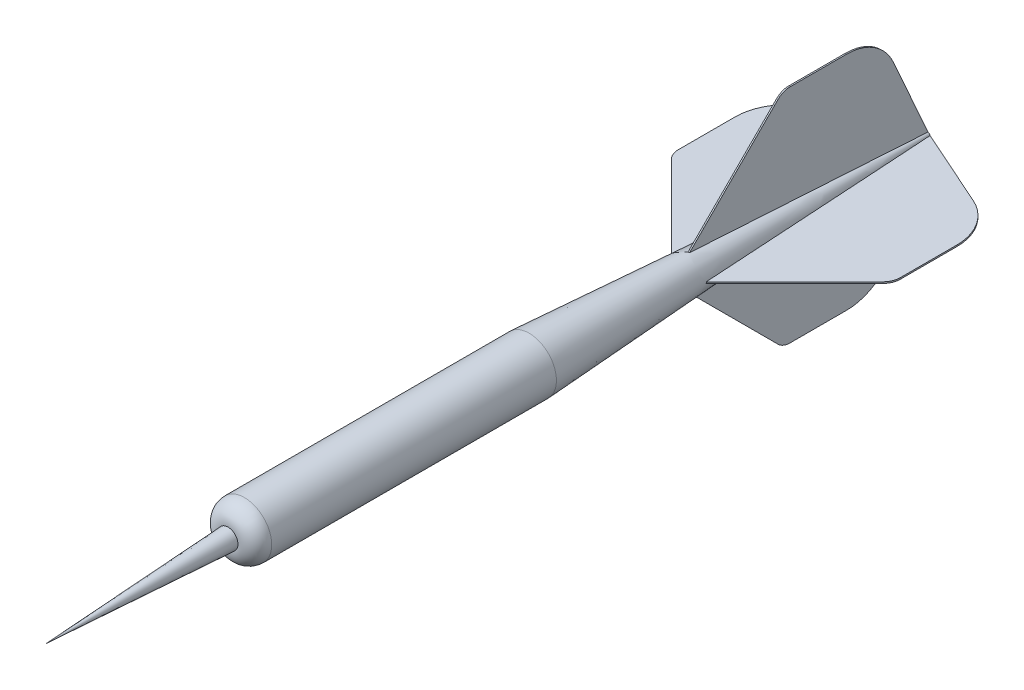
SolidWorks part; units mm, degrees
ref_plane "Front" through (0, 0, 0) normal (0, 0, 1) x (1, 0, 0)
ref_plane "Top" through (0, 0, 0) normal (0, 1, 0) x (1, 0, 0)
ref_plane "Right" through (0, 0, 0) normal (1, 0, 0) x (0, 0, -1)
sketch "Sketch1" plane through (0, 0, 0) normal (1, 0, 0) x (0, 0, -1)
  line L0 (0, 0) -> (-32, 0)
  line L1 (-32, 0) -> (0, 1.75)
  line L2 (2.8878, 4.8) -> (52.94, 4.8)
  line L3 (52.94, 4.8) -> (122.94, 0.5)
  line L4 (122.94, 0.5) -> (122.94, 0)
  line L5 (122.94, 0) -> (0, 0)
  line L6 (-32, 0) -> (-39.4145, 0) construction
  arc A0 (0, 1.75) -> (2.8878, 4.8) centre (2.8878, 1.9079) cw
  point P6 (0, 2.3209)
  point P10 (-39.4145, 0)
  dimension "D1" = 154.94
  dimension "D2" = 0.5
  dimension "D3" = 3.5
  dimension "D4" = 9.6
  dimension "D5" = 32
  dimension "D6" = 70
revolve "Dart" add sketch "Sketch1" angle 360 about L5
sketch "Sketch3" plane through (0, 0, 0) normal (1, 0, 0) x (0, 0, -1)
  line L0 (77.94, 0) -> (96.5613, 18.6213)
  line L1 (122.94, 0) -> (209.5416, 0) construction
  line L2 (98.6826, 19.5) -> (108.636, 19.5)
  line L4 (122.94, 0) -> (77.94, 0)
  line L5 (116.8579, 14.1606) -> (122.94, 0.5)
  line L6 (122.94, 0.5) -> (122.94, 0)
  line L7 (122.94, -0.5) -> (122.94, 0.5) construction
  arc A0 (96.5613, 18.6213) -> (98.6826, 19.5) centre (98.6826, 16.5) cw
  arc A1 (108.636, 19.5) -> (116.8579, 14.1606) centre (108.636, 10.5) cw
  point P0 (117.1222, 14.1125)
  dimension "D3" = 3
  dimension "D6" = 9
  dimension "D1" = 39
  dimension "D2" = 45
  dimension "D4" = 45
  dimension "D5" = 66
extrude "Flight" add sketch "Sketch3" along normal mid plane 0.25
pattern_circular "Flights" count 4 over 360 about axis through (0, 0, 0) along (0, 0, 1) of "Flight"
sketch "Sketch4" plane through (0, 0, 0) normal (0, 0, 1) x (1, 0, 0)
  line L0 (15.5733, 0) -> (0, 0) construction
  line L1 (0, 0) -> (14.4278, 14.4278) construction
  dimension "D1" = 45
sketch "Sketch6" plane through (0, 0, 0) normal (1, 0, 0) x (0, 0, -1)
  line L0 (0, 0) -> (21.0498, 0) construction
ref_plane "45 Degreen Plane" through (0, 0, 0) normal (-0.7071, 0.7071, 0) x (0.7071, 0.7071, 0)
sketch "Pocket Guide" plane through (0, 0, 0) normal (0, 0, 1) x (1, 0, 0)
  line L0 (0, 20) -> (0, 0) construction
  line L1 (0, 0) -> (20, 0) construction
  line L2 (-0.05, 20) -> (0.05, 20)
  line L3 (-0.75, 5.099) -> (-0.75, 19.3)
  line L4 (0.75, 19.3) -> (0.75, 5.099)
  line L5 (20, 0.05) -> (20, -0.05)
  line L6 (19.3, -0.75) -> (5.099, -0.75)
  line L7 (19.3, 0.75) -> (5.099, 0.75)
  line L8 (-5.099, 0.75) -> (-19.3, 0.75)
  line L9 (-20, 0.05) -> (-20, -0.05)
  line L10 (-19.3, -0.75) -> (-5.099, -0.75)
  line L11 (0.75, -5.099) -> (0.75, -19.3)
  line L12 (0.05, -20) -> (-0.05, -20)
  line L13 (-0.75, -19.3) -> (-0.75, -5.099)
  arc A0 (-4.6134, -1.131) -> (-1.131, -4.6134) centre (0, 0) ccw
  arc A1 (1.131, -4.6134) -> (4.6134, -1.131) centre (0, 0) ccw
  arc A2 (4.6134, 1.131) -> (1.131, 4.6134) centre (0, 0) ccw
  arc A3 (-1.131, 4.6134) -> (-4.6134, 1.131) centre (0, 0) ccw
  arc A4 (-0.05, 20) -> (-0.75, 19.3) centre (-0.05, 19.3) ccw
  arc A5 (0.05, 20) -> (0.75, 19.3) centre (0.05, 19.3) cw
  arc A6 (20, 0.05) -> (19.3, 0.75) centre (19.3, 0.05) ccw
  arc A7 (20, -0.05) -> (19.3, -0.75) centre (19.3, -0.05) cw
  arc A8 (0.75, -19.3) -> (0.05, -20) centre (0.05, -19.3) cw
  arc A9 (-0.05, -20) -> (-0.75, -19.3) centre (-0.05, -19.3) cw
  arc A10 (-20, -0.05) -> (-19.3, -0.75) centre (-19.3, -0.05) ccw
  arc A11 (-19.3, 0.75) -> (-20, 0.05) centre (-19.3, 0.05) ccw
  arc A12 (-0.75, 5.099) -> (-1.131, 4.6134) centre (-1.25, 5.099) cw
  arc A13 (0.75, 5.099) -> (1.131, 4.6134) centre (1.25, 5.099) ccw
  arc A14 (5.099, 0.75) -> (4.6134, 1.131) centre (5.099, 1.25) cw
  arc A15 (5.099, -0.75) -> (4.6134, -1.131) centre (5.099, -1.25) ccw
  arc A16 (0.75, -5.099) -> (1.131, -4.6134) centre (1.25, -5.099) cw
  arc A17 (-0.75, -5.099) -> (-1.131, -4.6134) centre (-1.25, -5.099) ccw
  arc A18 (-5.099, -0.75) -> (-4.6134, -1.131) centre (-5.099, -1.25) cw
  arc A19 (-5.099, 0.75) -> (-4.6134, 1.131) centre (-5.099, 1.25) ccw
  point P30 (20, 0.75)
  point P33 (20, -0.75)
  point P44 (-0.75, 4.6904)
  point P47 (0.75, 4.6904)
  point P50 (4.6904, 0.75)
  point P53 (4.6904, -0.75)
  point P56 (0.75, -4.6904)
  dimension "D1" = 9.5
  dimension "D4" = 0.7
  dimension "D5" = 0.5
  dimension "D2" = 40
  dimension "D3" = 1.5
sketch "Pin Pocket Guide" plane through (0, 0, 0) normal (0, 0, 1) x (1, 0, 0)
  circle A0 centre (0, 0) radius 2.5
  dimension "D1" = 5
sketch "Shaft Pocket Guide" plane through (0, 0, 0) normal (0, 0, 1) x (1, 0, 0)
  circle A0 centre (0, 0) radius 4.75
